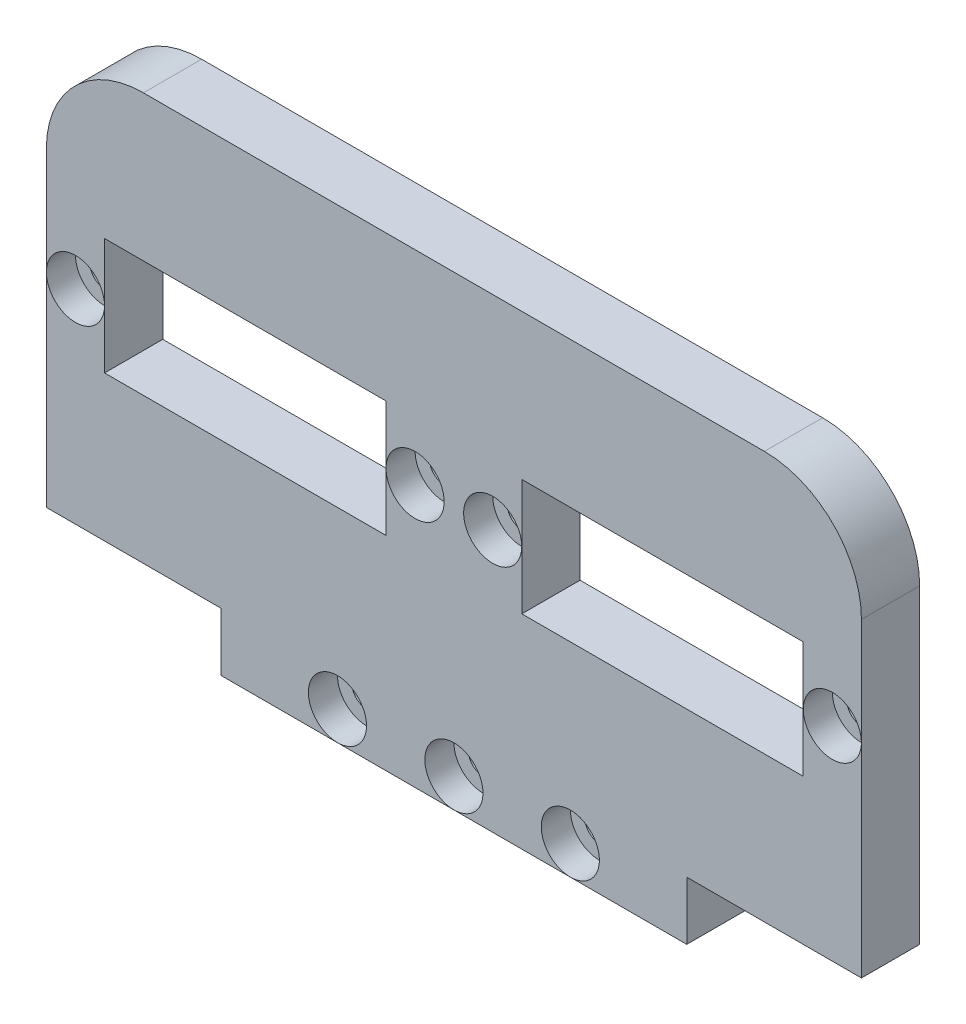
SolidWorks part; units mm, degrees
ref_plane "Plan de face" through (0, 0, 0) normal (0, 0, 1) x (1, 0, 0)
ref_plane "Plan de dessus" through (0, 0, 0) normal (0, 1, 0) x (1, 0, 0)
ref_plane "Plan de droite" through (0, 0, 0) normal (1, 0, 0) x (0, 0, -1)
sketch "Esquisse2" plane through (0, 0, 0) normal (0, 0, 1) x (1, 0, 0)
  line L1 (-31.4126, 34.1319) -> (52.5874, 34.1319)
  line L2 (-31.4126, 34.1319) -> (-31.4126, -13.8681)
  line L3 (-31.4126, -13.8681) -> (52.5874, -13.8681)
  line L4 (52.5874, 34.1319) -> (52.5874, -13.8681)
  dimension "D1" = 84
  dimension "D2" = 48
extrude "Boss.-Extru.1" add sketch "Esquisse2" along normal blind 6
sketch "Esquisse3" plane through (0, 0, 6) normal (0, 0, 1) x (1, 0, 0)
  line L0 (-31.4126, -13.8681) -> (52.5874, -13.8681) construction
  line L1 (-31.4126, -13.8681) -> (-13.4126, -13.8681)
  line L2 (-31.4126, -13.8681) -> (-31.4126, -7.8681)
  line L3 (-31.4126, -7.8681) -> (-13.4126, -7.8681)
  line L4 (-13.4126, -13.8681) -> (-13.4126, -7.8681)
  line L5 (52.5874, -13.8681) -> (34.5874, -13.8681)
  line L6 (52.5874, -13.8681) -> (52.5874, -7.8681)
  line L7 (52.5874, -7.8681) -> (34.5874, -7.8681)
  line L8 (34.5874, -13.8681) -> (34.5874, -7.8681)
  line L9 (-25.4126, 19.1319) -> (3.5874, 19.1319)
  line L10 (-25.4126, 19.1319) -> (-25.4126, 7.1319)
  line L11 (-25.4126, 7.1319) -> (3.5874, 7.1319)
  line L12 (3.5874, 19.1319) -> (3.5874, 7.1319)
  line L13 (17.5874, 19.1319) -> (46.5874, 19.1319)
  line L14 (17.5874, 19.1319) -> (17.5874, 7.1319)
  line L15 (17.5874, 7.1319) -> (46.5874, 7.1319)
  line L16 (46.5874, 19.1319) -> (46.5874, 7.1319)
  line L17 (-31.4126, 34.1319) -> (-31.4126, -13.8681) construction
  line L18 (52.5874, -13.8681) -> (52.5874, 34.1319) construction
  line L19 (52.5874, 34.1319) -> (-31.4126, 34.1319) construction
  line L20 (10.5874, -13.8681) -> (10.5874, -3.522) construction
  line L21 (-31.4126, -13.8681) -> (52.5874, -13.8681) construction
  circle A0 centre (-28.4126, 13.1319) radius 1.5
  circle A1 centre (49.5874, 13.1319) radius 1.5
  circle A2 centre (6.5874, 13.1319) radius 1.5
  circle A3 centre (14.5874, 13.1319) radius 1.5
  circle A4 centre (-1.4126, -10.8681) radius 1.5
  circle A5 centre (22.5874, -10.8681) radius 1.5
  circle A6 centre (10.5874, -10.8681) radius 1.5
  dimension "D14" = 3
  dimension "D15" = 3
  dimension "D16" = 3
  dimension "D17" = 3
  dimension "D18" = 21
  dimension "D19" = 21
  dimension "D20" = 3
  dimension "D21" = 3
  dimension "D22" = 3
  dimension "D23" = 3
  dimension "D24" = 3
  dimension "D25" = 3
  dimension "D26" = 12
  dimension "D29" = 3
  dimension "D1" = 18
  dimension "D2" = 18
  dimension "D3" = 48
  dimension "D4" = 6
  dimension "D5" = 6
  dimension "D6" = 15
  dimension "D7" = 6
  dimension "D8" = 6
  dimension "D9" = 15
  dimension "D10" = 29
  dimension "D11" = 12
  dimension "D12" = 29
  dimension "D13" = 12
  dimension "D27" = 6
  dimension "D28" = 6
  dimension "D30" = 0
extrude "Enlèv. mat.-Extru.1" cut sketch "Esquisse3" against normal blind 6
sketch "Esquisse4" plane through (0, 0, 6) normal (0, 0, 1) x (1, 0, 0)
  circle A0 centre (-1.4126, -10.8681) radius 2.995
  circle A1 centre (22.5874, -10.8681) radius 2.995
  circle A3 centre (10.5874, -10.8681) radius 2.995
  circle A4 centre (-28.4126, 13.1319) radius 2.995
  circle A5 centre (6.5874, 13.1319) radius 2.995
  circle A6 centre (14.5874, 13.1319) radius 2.995
  circle A7 centre (49.5874, 13.1319) radius 2.995
  dimension "D1" = 5.99
  dimension "D2" = 5.99
  dimension "D3" = 5.99
  dimension "D4" = 5.99
  dimension "D5" = 5.99
  dimension "D6" = 5.99
  dimension "D7" = 5.99
extrude "Enlèv. mat.-Extru.2" cut sketch "Esquisse4" against normal blind 3
fillet "Congé1" radius 10 2 edges at (52.5874, 34.1319, 3) (-31.4126, 34.1319, 3)
